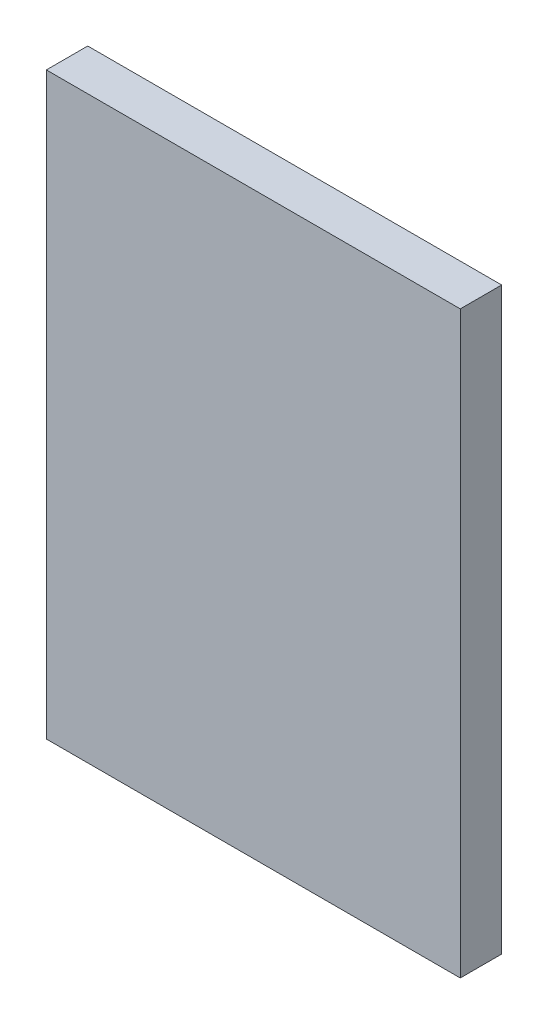
SolidWorks part; units mm, degrees
material "Pino"
ref_plane "Alzado" through (0, 0, 0) normal (0, 0, 1) x (1, 0, 0)
ref_plane "Planta" through (0, 0, 0) normal (0, 1, 0) x (1, 0, 0)
ref_plane "Vista lateral" through (0, 0, 0) normal (1, 0, 0) x (0, 0, -1)
sketch "Croquis2" plane through (0, 0, 0) normal (0, 0, 1) x (1, 0, 0)
  line L1 (0, 0) -> (500, 0)
  line L2 (0, 0) -> (0, 700)
  line L3 (0, 700) -> (500, 700)
  line L4 (500, 0) -> (500, 700)
  dimension "D1" = 700
  dimension "D2" = 500
extrude "Saliente-Extruir1" add sketch "Croquis2" along normal blind 50
